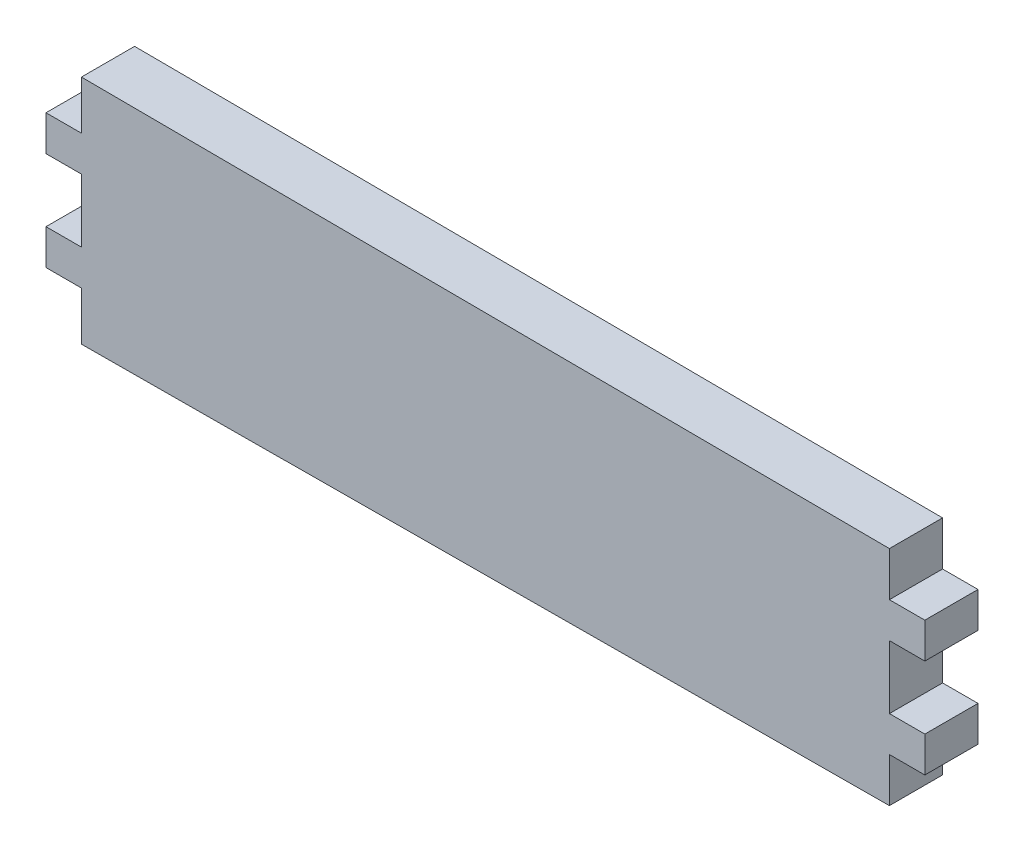
SolidWorks part; units mm, degrees
material "Balsa"
ref_plane "Front Plane" through (0, 0, 0) normal (0, 0, 1) x (1, 0, 0)
ref_plane "Top Plane" through (0, 0, 0) normal (0, 1, 0) x (1, 0, 0)
ref_plane "Right Plane" through (0, 0, 0) normal (1, 0, 0) x (0, 0, -1)
sketch "Sketch1" plane through (0, 0, 0) normal (0, 0, 1) x (1, 0, 0)
  line L0 (220.1079, -23.3215) -> (216.9329, -23.3215)
  line L1 (216.9329, -23.3215) -> (216.9329, -26.4965)
  line L2 (216.9329, -26.4965) -> (220.1079, -26.4965)
  line L3 (220.1079, -26.4965) -> (220.1079, -32.1607)
  line L4 (220.1079, -32.1607) -> (216.9329, -32.1607)
  line L5 (216.9329, -32.1607) -> (216.9329, -35.3357)
  line L6 (216.9329, -35.3357) -> (220.1079, -35.3357)
  line L7 (220.1079, -35.3357) -> (220.1079, -39.6936)
  line L8 (220.1079, -23.3215) -> (220.1079, -18.9637)
  line L9 (292.4979, -23.3215) -> (295.6729, -23.3215)
  line L10 (295.6729, -23.3215) -> (295.6729, -26.4965)
  line L11 (295.6729, -26.4965) -> (292.4979, -26.4965)
  line L12 (292.4979, -26.4965) -> (292.4979, -32.1607)
  line L13 (292.4979, -32.1607) -> (295.6729, -32.1607)
  line L14 (295.6729, -32.1607) -> (295.6729, -35.3357)
  line L15 (295.6729, -35.3357) -> (292.4979, -35.3357)
  line L16 (292.4979, -35.3357) -> (292.4979, -39.3024)
  line L17 (292.4979, -39.3024) -> (220.1079, -39.6936)
  line L18 (292.4979, -23.3215) -> (292.4979, -19.3546)
  line L19 (292.4979, -19.3546) -> (220.1079, -18.9637)
extrude "Boss-Extrude1" add sketch "Sketch1" along normal up to surface (4.7625 mm away)
